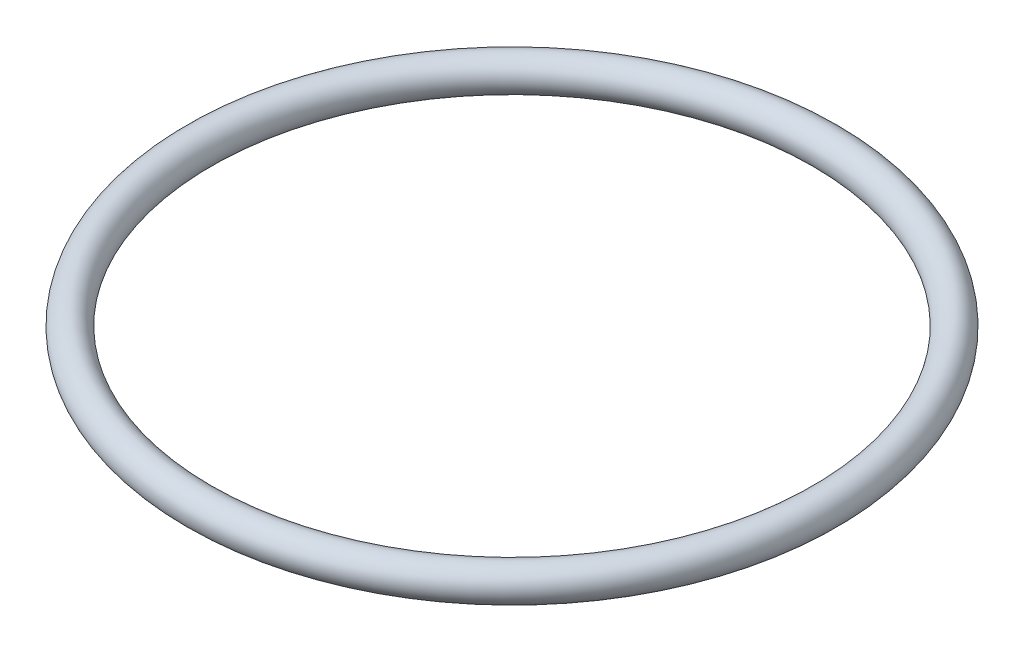
SolidWorks part; units mm, degrees
ref_plane "Front Plane" through (0, 0, 0) normal (0, 0, 1) x (1, 0, 0)
ref_plane "Top Plane" through (0, 0, 0) normal (0, 1, 0) x (1, 0, 0)
ref_plane "Right Plane" through (0, 0, 0) normal (1, 0, 0) x (0, 0, -1)
sketch "Reconstructed nominal axial profile" plane through (0, 0, 0) normal (0, 0, 1) x (1, 0, 0)
  line L0 (0, -500) -> (0, 50) construction
  circle A0 centre (18.5, 0) radius 1
revolve "Native revolved geometry" add sketch "Reconstructed nominal axial profile" angle 360 about L0
